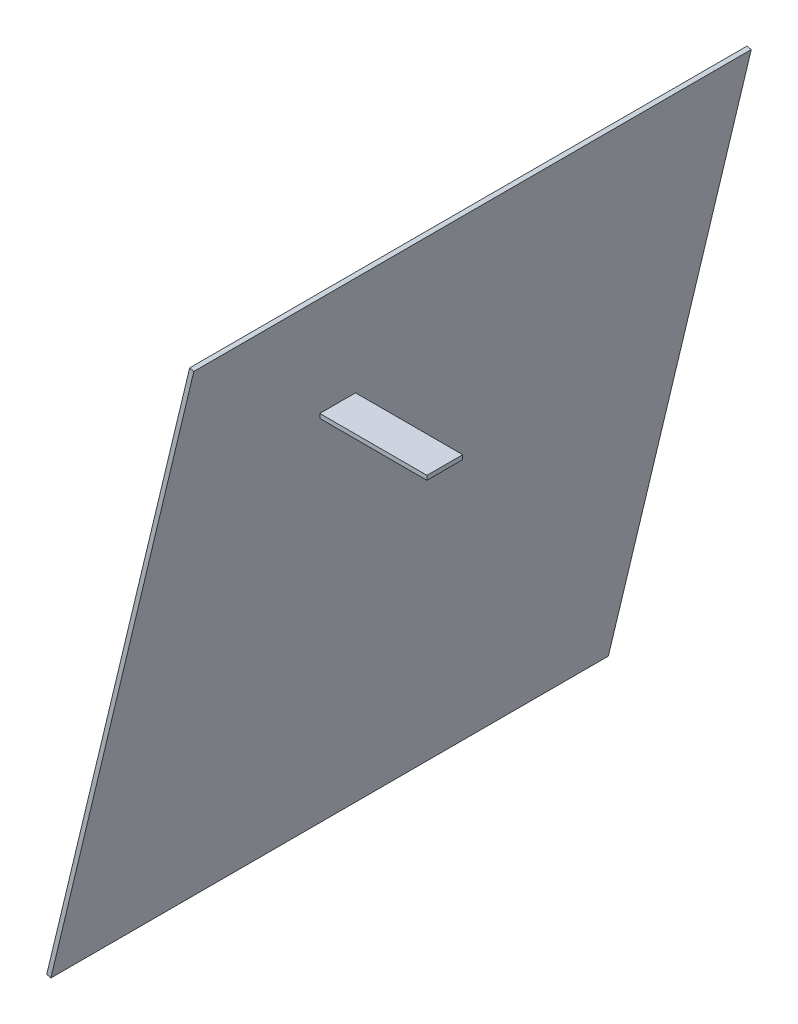
SolidWorks part; units mm, degrees
ref_plane "Front Plane" through (0, 0, 0) normal (0, 0, 1) x (1, 0, 0)
ref_plane "Top Plane" through (0, 0, 0) normal (0, 1, 0) x (1, 0, 0)
ref_plane "Right Plane" through (0, 0, 0) normal (1, 0, 0) x (0, 0, -1)
sketch "Sketch2" plane through (0, 0, 0) normal (1, 0, 0) x (0, 0, -1)
  line L0 (1.0445, -376.4417) -> (1.0445, 41.0783) construction
  line L1 (1.0445, 41.0783) -> (391.0445, 41.0783) construction
  line L2 (196.0445, 41.0783) -> (196.0445, -90.53) construction
  dimension "D1" = 417.52
  dimension "D2" = 390
ref_plane "Plane1" through (0, 0, 0) normal (1, 0, 0) x (0, 0, -1)
ref_plane "Plane2" through (0, 41.0783, 0) normal (0, -1, 0) x (0, 0, -1)
sketch "Sketch3" plane through (0, 41.0783, 0) normal (0, -1, 0) x (0, 0, -1)
  line L0 (1.0445, 0) -> (1.0445, 100) construction
  line L1 (1.0445, 100) -> (40.0445, 100) construction
  dimension "D1" = 100
ref_plane "Plane3" through (85.2699, -20.4229, 0) normal (-0.9725, 0.2329, 0) x (0, 0, 1)
sketch "Sketch4" plane through (85.2699, -20.4229, 0) normal (-0.9725, 0.2329, 0) x (0, 0, 1)
  line L1 (-1.0445, -366.0878) -> (-391.0445, -366.0878)
  line L2 (-1.0445, -366.0878) -> (-1.0445, 63.2406)
  line L3 (-1.0445, 63.2406) -> (-391.0445, 63.2406)
  line L4 (-391.0445, -366.0878) -> (-391.0445, 63.2406)
  dimension "D1" = 390
extrude "Boss-Extrude1" add sketch "Sketch4" along normal blind 3
sketch "Sketch5" plane through (85.2699, -20.4229, 0) normal (-0.9725, 0.2329, 0) x (0, 0, 1)
  line L0 (-1.0445, 63.2406) -> (-111.0445, 63.2406) construction
  line L1 (-1.0445, 63.2406) -> (-391.0445, 63.2406) construction
  line L2 (-111.0445, 63.2406) -> (-111.0445, -30.7594) construction
  dimension "D1" = 110
  dimension "D2" = 94
ref_plane "Plane4" through (0, -50.3363, 0) normal (0, -1, 0) x (1, 0, 0)
sketch "Sketch7" plane through (0, -50.3363, 0) normal (0, -1, 0) x (1, 0, 0)
  line L1 (78.1053, -111.0445) -> (153.1053, -111.0445)
  line L2 (78.1053, -111.0445) -> (78.1053, -136.0445)
  line L3 (78.1053, -136.0445) -> (153.1053, -136.0445)
  line L4 (153.1053, -111.0445) -> (153.1053, -136.0445)
  dimension "D1" = 75
  dimension "D2" = 25
extrude "Boss-Extrude2" add sketch "Sketch7" along normal blind 3 separate body
